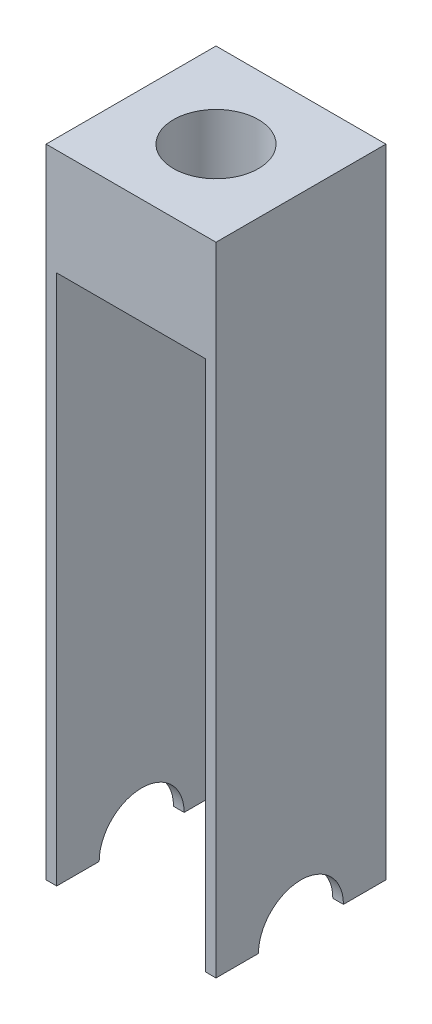
SolidWorks part; units mm, degrees
ref_plane "Front Plane" through (0, 0, 0) normal (0, 0, 1) x (1, 0, 0)
ref_plane "Top Plane" through (0, 0, 0) normal (0, 1, 0) x (1, 0, 0)
ref_plane "Right Plane" through (0, 0, 0) normal (1, 0, 0) x (0, 0, -1)
sketch "Sketch2" plane through (0, 0, 0) normal (1, 0, 0) x (0, 0, -1)
  line L0 (-20, -150) -> (-40, -150)
  line L1 (40, -150) -> (20, -150)
  line L2 (40, -150) -> (40, 150)
  line L3 (40, 150) -> (-40, 150)
  line L4 (-40, -150) -> (-40, 150)
  line L5 (40, -150) -> (-40, 150) construction
  line L6 (40, 150) -> (-40, -150) construction
  arc A0 (20, -150) -> (-20, -150) centre (0, -150) ccw
  point P0 (0, 0)
  dimension "D3" = 40
  dimension "D1" = 80
  dimension "D2" = 300
extrude "Boss-Extrude1" add sketch "Sketch2" along normal blind 80
sketch "Sketch3" plane through (0, 0, 40) normal (0, 0, 1) x (1, 0, 0)
  line L0 (80, -150) -> (0, -150) construction
  line L1 (5, 100) -> (75, 100)
  line L2 (5, 100) -> (5, -150)
  line L3 (5, -150) -> (75, -150)
  line L4 (75, 100) -> (75, -150)
  line L5 (0, 150) -> (0, -150) construction
  dimension "D1" = 70
  dimension "D2" = 5
  dimension "D3" = 250
extrude "Cut-Extrude1" cut sketch "Sketch3" against normal through all
sketch "Sketch4" plane through (0, 150, 0) normal (0, 1, 0) x (1, 0, 0)
  line L0 (0, 40) -> (0, -40) construction
  line L3 (80, 40) -> (0, 40) construction
  circle A0 centre (40, 0) radius 20
  point P6 (40.0059, 40)
  point P7 (51.6181, 40)
  point P8 (0, 0)
  point P10 (59.4597, -4.6172)
  dimension "D1" = 40
  dimension "D2" = 40
  dimension "D3" = 40
extrude "Cut-Extrude2" cut sketch "Sketch4" against normal blind 40
